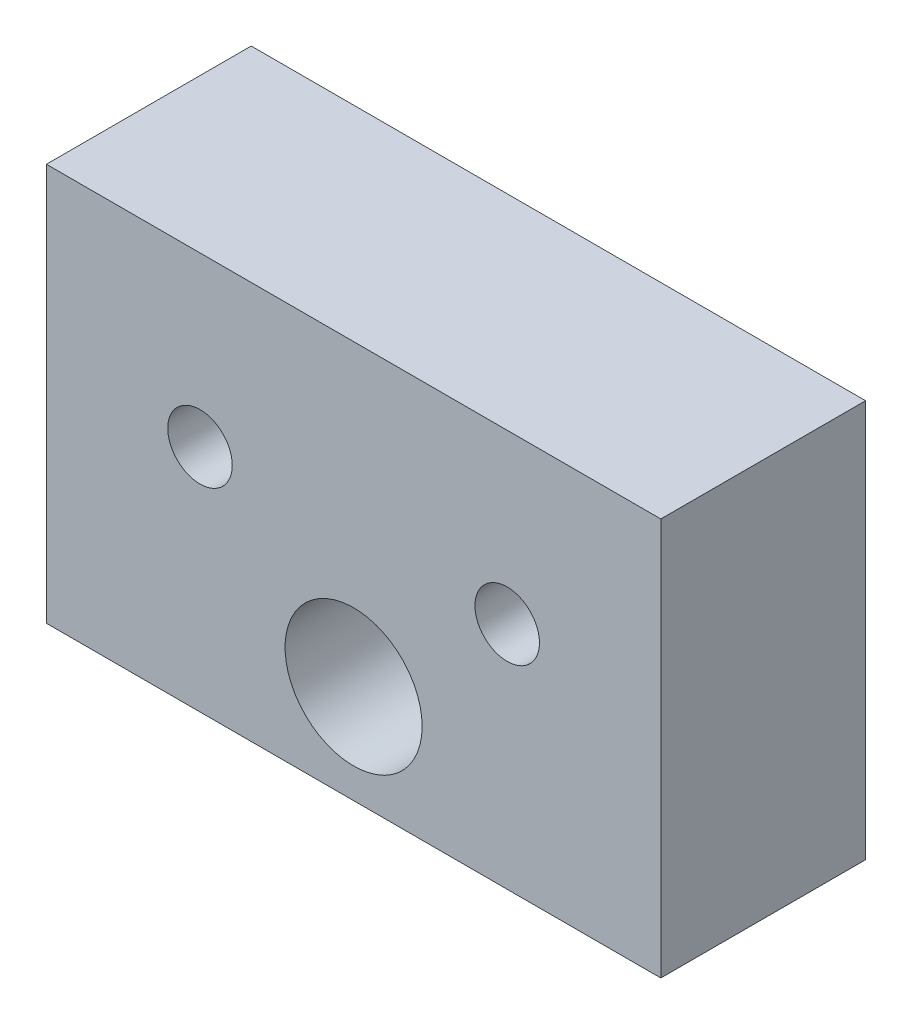
SolidWorks part; units mm, degrees
material "Acrylic (Medium-high impact)"
ref_plane "Front Plane" through (0, 0, 0) normal (0, 0, 1) x (1, 0, 0)
ref_plane "Top Plane" through (0, 0, 0) normal (0, 1, 0) x (1, 0, 0)
ref_plane "Right Plane" through (0, 0, 0) normal (1, 0, 0) x (0, 0, -1)
sketch "Sketch1" plane through (0, 0, 0) normal (0, 0, 1) x (1, 0, 0)
  line L2 (38.1, -12.224) -> (38.1, 12.224)
  line L4 (-38.1, -12.224) -> (-38.1, 12.224)
  line L8 (-38.1, -12.224) -> (38.1, -12.224)
  line L11 (-38.1, 37.084) -> (-38.1, 12.224)
  line L12 (38.1, 12.224) -> (38.1, 37.084)
  line L13 (-38.1, 37.084) -> (-38.1, 49.2259)
  line L14 (-38.1, 37.084) -> (38.1, 37.084)
  line L16 (-38.1, 49.2259) -> (38.1, 49.2259)
  line L18 (38.1, 37.084) -> (38.1, 49.2259)
  circle A0 centre (0, 0) radius 8.5
  circle A1 centre (19.05, 16.256) radius 4
  circle A2 centre (-19.05, 16.256) radius 4
  point P0 (0, 0)
  point P6 (-38.1, 0)
  dimension "D3" = 17
  dimension "D4" = 8
  dimension "D1" = 76.2
  dimension "D2" = 20.828
  dimension "D5" = 19.05
  dimension "D6" = 16.256
  dimension "D7" = 19.05
  dimension "D8" = 61.4499
  dimension "D9" = 76.2
extrude "Boss-Extrude1" add sketch "Sketch1" along normal mid plane 25.4 contours L14 L11 L4 L8 L2 L12 A2 A1 A0
